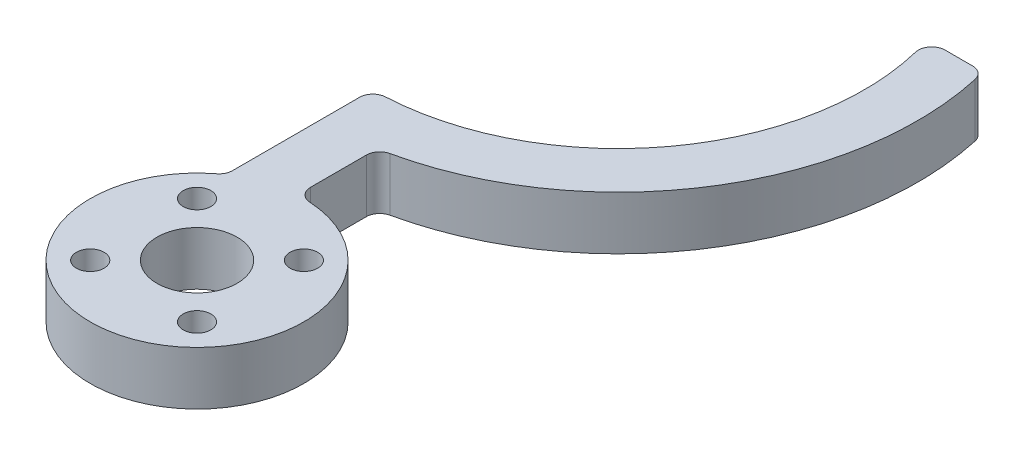
SolidWorks part; units mm, degrees
ref_plane "Front Plane" through (0, 0, 0) normal (0, 0, 1) x (1, 0, 0)
ref_plane "Top Plane" through (0, 0, 0) normal (0, 1, 0) x (1, 0, 0)
ref_plane "Right Plane" through (0, 0, 0) normal (1, 0, 0) x (0, 0, -1)
sketch "Sketch1" plane through (0, 0, 0) normal (0, 1, 0) x (1, 0, 0)
  line L0 (0, 44.83) -> (0, 36.83)
  line L1 (0, -36.83) -> (0, -46.83)
  line L2 (0, -46.83) -> (0, -58.83)
  line L3 (8, -44.1104) -> (8, -56.1104)
  line L8 (16.967, -80.0812) -> (0.967, -80.0812) construction
  line L13 (16.967, -80.0812) -> (16.967, -64.0812) construction
  line L21 (16.967, -64.0812) -> (0.967, -64.0812) construction
  line L22 (0.967, -80.0812) -> (0.967, -64.0812) construction
  line L23 (16.967, -80.0812) -> (0.967, -64.0812) construction
  line L24 (16.967, -64.0812) -> (0.967, -80.0812) construction
  arc A0 (0, -36.83) -> (0, 36.83) centre (0, 0) ccw
  arc A1 (8, -44.1104) -> (0, 44.83) centre (0, 0) ccw
  arc A7 (0, -58.83) -> (23.0776, -79.6236) centre (8.967, -72.0812) ccw
  circle A8 centre (0.967, -64.0812) radius 2.075
  circle A9 centre (16.967, -64.0812) radius 2.075
  circle A10 centre (16.967, -80.0812) radius 2.075
  circle A11 centre (0.967, -80.0812) radius 2.075
  arc A12 (0, -58.83) -> (8, -56.1104) centre (8.967, -72.0812) ccw
  circle A13 centre (8.967, -72.0812) radius 6.0032
  dimension "D1" = 73.66
  dimension "D8" = 4.15
  dimension "D6" = 16
  dimension "D2" = 8
  dimension "D3" = 8
  dimension "D4" = 12
  dimension "D9" = 10
  dimension "D7" = 16
  dimension "D5" = 12
extrude "Boss-Extrude2" add sketch "Sketch1" along normal blind 8 contours A7 A12 L3 A1 L0 A0 L1 L2 A8 A9 A10 A11
fillet "Fillet1" radius 2 6 edges at (0, 4, -36.83) (0, 4, -44.83) (8, 4, 56.1104) (8, 4, 44.1104) (0, 4, 58.83) (0, 4, 36.83)
sketch "Sketch2" plane through (0, 8, 0) normal (0, 1, 0) x (1, 0, 0)
  line L0 (0, 44.7833) -> (0, -43.796) construction
  line L1 (9.5729, -43.796) -> (0, -43.796) construction
  line L2 (0, -38.7785) -> (0, -57.8079) construction
  line L3 (0, 16.204) -> (0, -43.796) construction
  line L4 (0, 16.204) -> (41.799, 16.204) construction
  line L5 (41.799, 16.204) -> (33.0738, 16.204)
  line L6 (0, 42.7833) -> (0, 38.7785)
  line L8 (0, 44.7833) -> (0, 42.7833)
  line L9 (2.7521, 44.7829) -> (2.7521, 46.6557)
  line L10 (2.7521, 46.6557) -> (-0.2578, 46.6557)
  line L11 (-0.2578, 46.6557) -> (0, 44.7833)
  arc A0 (9.5729, -43.796) -> (2.0934, 44.7811) centre (0, 0) ccw construction
  arc A1 (1.897, -36.7811) -> (1.897, 36.7811) centre (0, 0) ccw construction
  arc A2 (2.7521, 44.7829) -> (41.799, 16.204) centre (2.3579, 3.2803) cw
  arc A3 (2.0934, 44.7811) -> (0, 42.7833) centre (2, 42.7833) ccw construction
  arc A4 (33.0738, 16.204) -> (1.897, 36.7811) centre (0, 0) ccw
  arc A6 (1.897, 36.7811) -> (0, 38.7785) centre (2, 38.7785) cw
extrude "Cut-Extrude1" cut sketch "Sketch2" against normal blind 10
fillet "Fillet2" radius 2 2 edges at (41.799, 4, -16.204) (33.0738, 4, -16.204)
sketch "Sketch3" plane through (0, 8, 0) normal (0, 1, 0) x (1, 0, 0)
  line L0 (9.5729, -43.796) -> (0, -43.796) construction
  line L1 (34.7016, 11.204) -> (33.2223, 16.5708)
  line L2 (0, -38.7785) -> (0, -57.8079) construction
  line L3 (9.5729, -43.796) -> (9.5729, 11.204) construction
  line L4 (33.2223, 16.5708) -> (43.8921, 17.2665)
  line L5 (9.5729, 11.204) -> (34.7016, 11.204) construction
  line L6 (43.8921, 17.2665) -> (44.7337, 11.204)
  line L11 (44.7337, 11.204) -> (34.7016, 11.204)
  point P2 (34.7016, 11.204)
  dimension "D1" = 55
extrude "Cut-Extrude2" cut sketch "Sketch3" against normal blind 10
fillet "Fillet3" radius 2 2 edges at (43.4074, 4, -11.204) (35.0845, 4, -11.204)
equation "\"innerSmall\"= 2.9in"
equation "\"thick\"= 8mm"
equation "\"D1@Sketch1\"=\"innerSmall\""
equation "\"D2@Sketch1\"=\"thick\""
equation "\"D3@Sketch1\"=\"thick\""
equation "\"D7@Sketch1\"=16mm"
equation "\"height\"=55"
equation "\"D1@Sketch3\"=\"height\""
